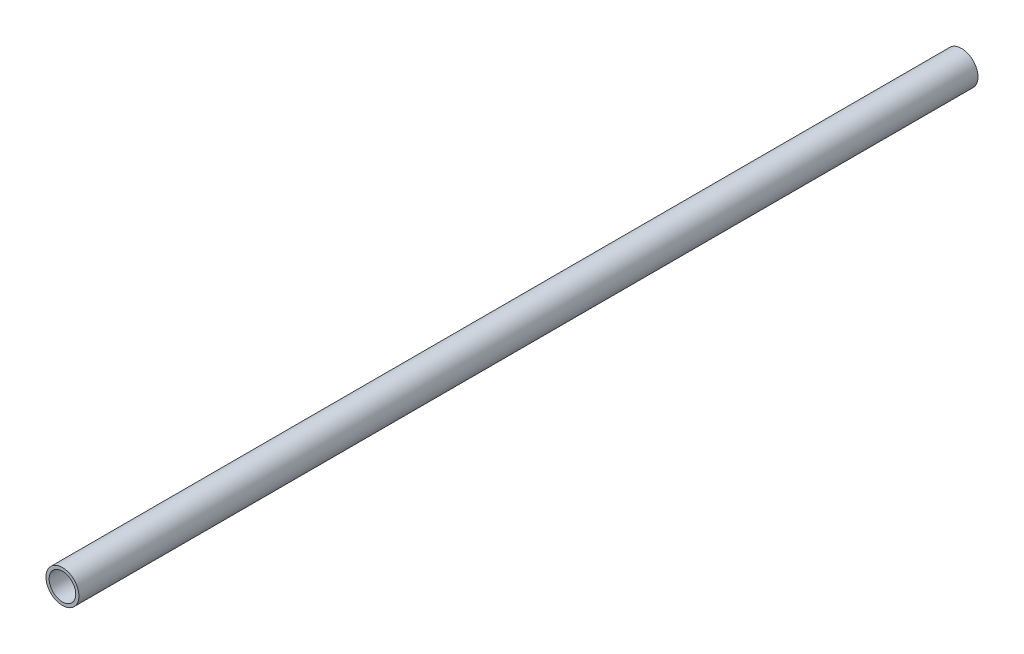
SolidWorks part; units mm, degrees
ref_plane "Front Plane" through (0, 0, 0) normal (0, 0, 1) x (1, 0, 0)
ref_plane "Top Plane" through (0, 0, 0) normal (0, 1, 0) x (1, 0, 0)
ref_plane "Right Plane" through (0, 0, 0) normal (1, 0, 0) x (0, 0, -1)
sketch "Sketch1" plane through (0, 0, 0) normal (0, 0, 1) x (1, 0, 0)
  circle A0 centre (0, 0) radius 5
  circle A1 centre (0, 0) radius 4.05
  dimension "D1" = 10
  dimension "D2" = 8.1
extrude "Boss-Extrude1" add sketch "Sketch1" along normal blind 273
